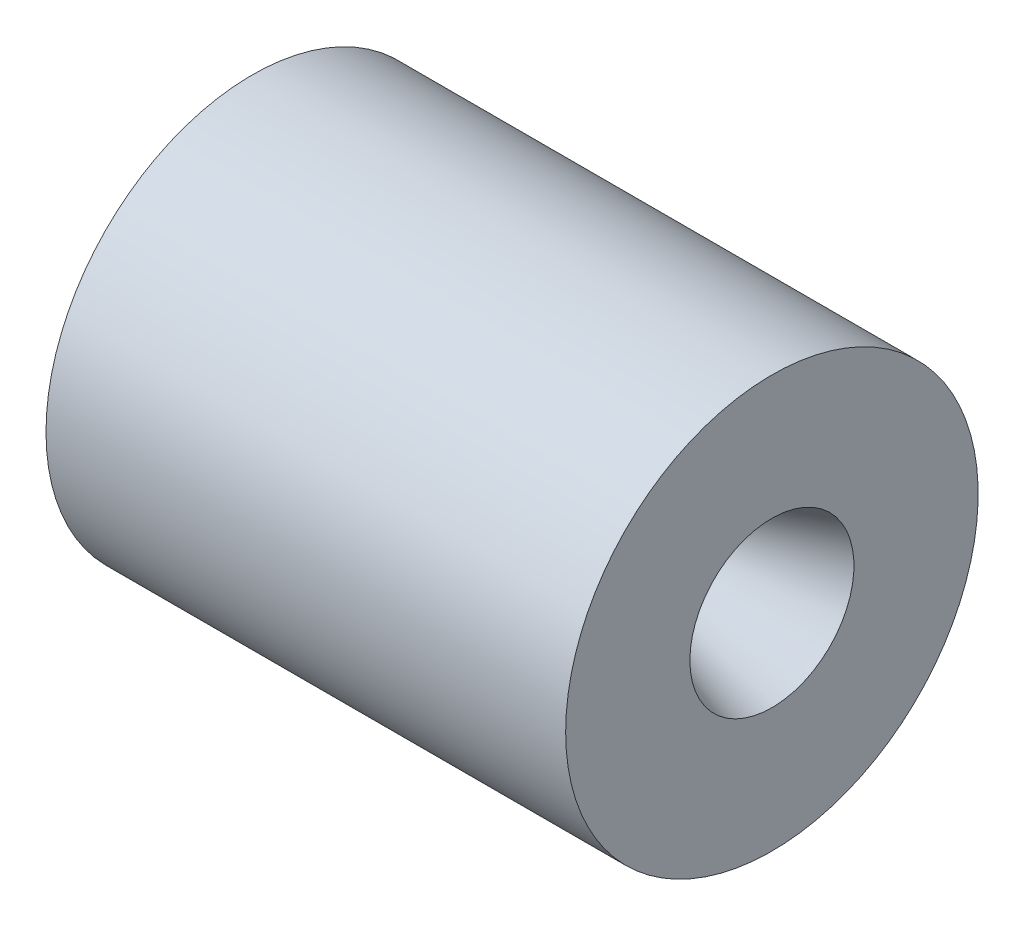
SolidWorks part; units mm, degrees
ref_plane "Front Plane" through (0, 0, 0) normal (0, 0, 1) x (1, 0, 0)
ref_plane "Top Plane" through (0, 0, 0) normal (0, 1, 0) x (1, 0, 0)
ref_plane "Right Plane" through (0, 0, 0) normal (1, 0, 0) x (0, 0, -1)
sketch "Model" plane through (0, 0, 0) normal (0, 0, 1) x (1, 0, 0)
  line L0 (0, 56.4998) -> (23.7217, 56.4998)
  line L1 (97.4974, 36.7316) -> (131.7368, 16.9635)
  line L2 (0, 0) -> (190.2264, 0) construction
  line L3 (0, 56.4998) -> (0, 75.4998)
  line L4 (0, 75.4998) -> (190.2264, 75.4998)
  line L5 (190.2264, 75.4998) -> (190.2264, 30.0329)
  arc A0 (97.4974, 36.7316) -> (23.7217, 56.4998) centre (23.7217, -91.0515) ccw
  arc A1 (131.7368, 16.9635) -> (142.3305, 14.1249) centre (142.3305, 35.3124) ccw
  arc A2 (142.3305, 14.1249) -> (144.0756, 14.4149) centre (142.3305, 19.5207) ccw
  spline S0 degree 2 poles (144.0756, 14.4149) (185.9341, 28.722) (190.2264, 30.0329) knots 0 0 0 1 1 1
  dimension "D1" = 19
  dimension "D2" = 56.4998
revolve "Revolve1" add sketch "Model" angle 360 about L2
